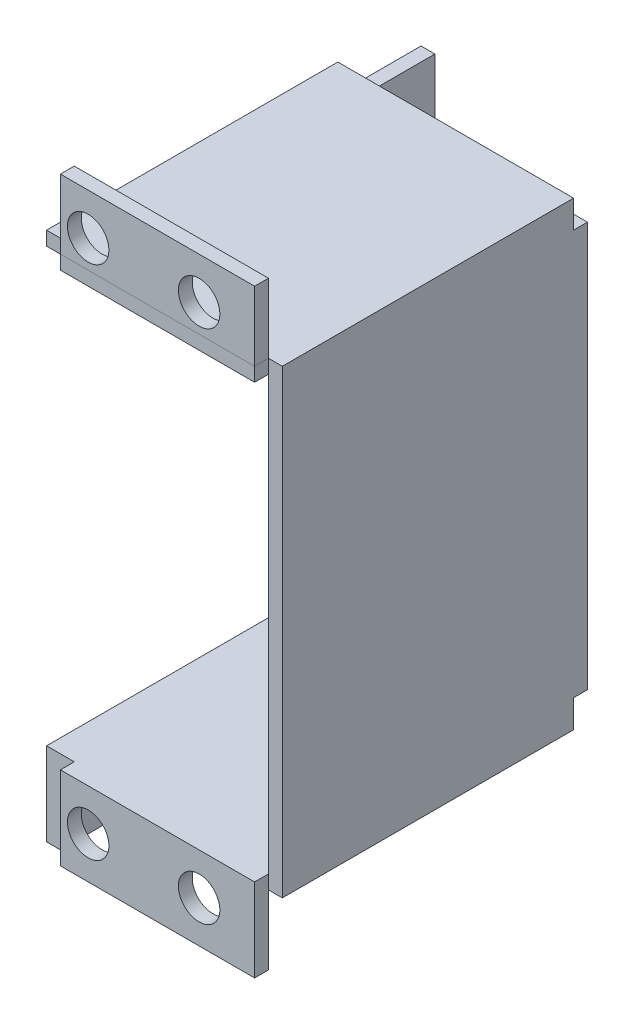
SolidWorks part; units mm, degrees
ref_plane "Front Plane" through (0, 0, 0) normal (0, 0, 1) x (1, 0, 0)
ref_plane "Top Plane" through (0, 0, 0) normal (0, 1, 0) x (1, 0, 0)
ref_plane "Right Plane" through (0, 0, 0) normal (1, 0, 0) x (0, 0, -1)
sketch "Sketch1" plane through (0, 0, 0) normal (0, 0, 1) x (1, 0, 0)
  line L1 (0, 0) -> (20.32, 0)
  line L2 (20.32, 0) -> (20.32, -39.624)
  line L3 (20.32, -39.624) -> (0, -39.624)
  line L4 (0, -39.624) -> (0, -47.244)
  dimension "D1" = 20.32
  dimension "D3" = 7.62
  dimension "D4" = 39.624
extrude "Extrude-Thin1" add sketch "Sketch1" along normal blind 26.67 thin thin type one direction reverse wall 1.27
hole_wizard "#6 Clearance Hole4" positions "Sketch13" profile "Sketch12" hole size "#6" standard "ANSI Inch"
sketch "Sketch13" plane through (1.27, 0, 0) normal (1, 0, 0) x (0, 0, -1)
  line L0 (-26.67, -40.894) -> (-26.67, -47.244) construction
  line L1 (0, -40.894) -> (0, -47.244) construction
  point P0 (-21.59, -44.069)
  point P2 (-5.08, -44.069)
  dimension "D1" = 5.08
  dimension "D2" = 5.08
sketch "Sketch12" plane through (1.27, -44.069, 21.59) normal (0, 1, 0) x (0, 0, -1)
  line L0 (0, 0) -> (0, 8.7608)
  line L1 (0, 8.7608) -> (1.8986, 7.62)
  line L2 (1.8986, 7.62) -> (1.8986, 0)
  line L5 (1.8986, 0) -> (0, 0)
  line L10 (0, 8.7608) -> (-1.8987, 7.62) construction
  line L11 (0, -6.35) -> (0, 107.95) construction
  dimension "Hole Dia." = 3.7973
  dimension "Hole Depth" = 7.62
  dimension "Drill Angle" = 118
sketch "Sketch4" plane through (0, 1.27, 0) normal (0, 1, 0) x (1, 0, 0)
  line L0 (0, -26.67) -> (21.59, -26.67) construction
  line L1 (2.54, -26.67) -> (20.32, -26.67)
  line L8 (2.54, -26.67) -> (2.54, -27.94)
  line L9 (20.32, -26.67) -> (20.32, -27.94)
  line L10 (20.32, -27.94) -> (2.54, -27.94)
  dimension "D4" = 1.27
extrude "Boss-Extrude1" add sketch "Sketch4" along normal blind 6.35
sketch "Sketch7" plane through (0, 0, 26.67) normal (0, 0, 1) x (1, 0, 0)
  line L0 (20.32, 1.27) -> (2.54, 1.27)
  line L1 (2.54, 1.27) -> (2.54, 0)
  line L2 (0, 0) -> (20.32, 0) construction
  line L3 (2.54, 0) -> (20.32, 0)
  line L4 (20.32, 0) -> (20.32, 1.27)
extrude "Boss-Extrude2" add sketch "Sketch7" along normal blind 1.27
hole_wizard "#6 Clearance Hole2" positions "Sketch6" profile "Sketch5" hole size "#6" standard "ANSI Inch" end condition through all
sketch "Sketch6" plane through (0, 0, 26.67) normal (0, 0, 1) x (1, 0, 0)
  line L1 (0, 0) -> (2.54, 0) construction
  line L3 (20.32, 7.62) -> (20.32, 1.27) construction
  point P0 (5.08, 3.81)
  point P2 (15.24, 3.81)
  dimension "D1" = 3.81
  dimension "D2" = 3.81
  dimension "D3" = 10.16
  dimension "D4" = 5.08
sketch "Sketch5" plane through (5.08, 3.81, 26.67) normal (1, 0, 0) x (0, 1, 0)
  line L0 (0, 0) -> (0, 1.27)
  line L1 (0, 1.27) -> (1.8986, 1.27)
  line L2 (1.8986, 1.27) -> (1.8986, 0)
  line L5 (1.8986, 0) -> (0, 0)
  line L11 (0, -6.35) -> (0, 107.95) construction
  dimension "Thru Hole Dia." = 3.7973
  dimension "Thru Hole Depth" = 1.27
sketch "Sketch8" plane through (0, 0, 26.67) normal (0, 0, 1) x (1, 0, 0)
  line L0 (20.32, -39.624) -> (2.54, -39.624)
  line L1 (20.32, -39.624) -> (0, -39.624) construction
  line L2 (2.54, -39.624) -> (2.54, -40.894)
  line L3 (21.59, -40.894) -> (1.27, -40.894) construction
  line L4 (2.54, -40.894) -> (20.32, -40.894)
  line L5 (20.32, -40.894) -> (20.32, -39.624)
  dimension "D1" = 17.78
extrude "Boss-Extrude3" add sketch "Sketch8" along normal blind 1.27
sketch "Sketch9" plane through (0, -40.894, 0) normal (0, -1, 0) x (1, 0, 0)
  line L1 (20.32, 27.94) -> (2.54, 27.94)
  line L2 (20.32, 27.94) -> (20.32, 26.67)
  line L3 (20.32, 26.67) -> (2.54, 26.67)
  line L4 (2.54, 27.94) -> (2.54, 26.67)
extrude "Boss-Extrude4" add sketch "Sketch9" along normal blind 6.35
hole_wizard "#6 Clearance Hole3" positions "Sketch11" profile "Sketch10" hole size "#6" standard "ANSI Inch"
sketch "Sketch11" plane through (0, 0, 27.94) normal (0, 0, 1) x (1, 0, 0)
  line L0 (20.32, -47.244) -> (20.32, -39.624) construction
  line L2 (20.32, -39.624) -> (2.54, -39.624) construction
  point P0 (15.24, -43.434)
  point P2 (5.08, -43.434)
  point P15 (15.24, -43.434)
  dimension "D1" = 5.08
  dimension "D2" = 10.16
  dimension "D3" = 3.81
sketch "Sketch10" plane through (15.24, -43.434, 27.94) normal (1, 0, 0) x (0, -1, 0)
  line L0 (0, 0) -> (0, 4.9508)
  line L1 (0, 4.9508) -> (1.8986, 3.81)
  line L2 (1.8986, 3.81) -> (1.8986, 0)
  line L5 (1.8986, 0) -> (0, 0)
  line L10 (0, 4.9508) -> (-1.8987, 3.81) construction
  line L11 (0, -6.35) -> (0, 107.95) construction
  dimension "Hole Dia." = 3.7973
  dimension "Hole Depth" = 3.81
  dimension "Drill Angle" = 118
sketch "Sketch15" plane through (0, 0, 0) normal (0, 0, -1) x (-1, 0, 0)
  line L1 (-20.32, -1.27) -> (-21.59, -1.27)
  line L2 (-20.32, -1.27) -> (-20.32, -38.354)
  line L3 (-20.32, -38.354) -> (-21.59, -38.354)
  line L4 (-21.59, -1.27) -> (-21.59, -38.354)
  line L6 (0, 1.27) -> (-21.59, 1.27) construction
  line L7 (-21.59, -40.894) -> (-1.27, -40.894) construction
  dimension "D1" = 2.54
  dimension "D2" = 2.54
extrude "Boss-Extrude5" add sketch "Sketch15" along normal blind 1.27
sketch "Sketch17" plane through (20.32, 0, 0) normal (-1, 0, 0) x (0, 0, 1)
  line L0 (-1.27, -38.354) -> (-1.27, -1.27) construction
  line L1 (-1.27, -1.27) -> (0, -1.27)
  line L2 (-1.27, -1.27) -> (-1.27, -38.354)
  line L3 (-1.27, -38.354) -> (0, -38.354)
  line L4 (0, -1.27) -> (0, -38.354)
  line L5 (-1.27, -1.27) -> (0, -1.27) construction
  line L6 (-1.27, -38.354) -> (0, -38.354) construction
  dimension "D1" = 0
  dimension "D2" = 0
extrude "Boss-Extrude14" add sketch "Sketch17" along normal blind 20.32 contours L4 L3 L2 L1
sketch "Sketch18" plane through (0, 0, -1.27) normal (0, 0, -1) x (-1, 0, 0)
  line L0 (-21.59, -38.354) -> (0, -38.354) construction
  line L1 (0, -1.27) -> (-1.27, -1.27)
  line L2 (0, -1.27) -> (0, -38.354)
  line L3 (0, -38.354) -> (-1.27, -38.354)
  line L4 (-1.27, -1.27) -> (-1.27, -38.354)
  dimension "D1" = 1.27
extrude "Boss-Extrude15" add sketch "Sketch18" along normal blind 6.35
hole_wizard "#6 Clearance Hole5" positions "Sketch20" profile "Sketch19" hole size "#6" standard "ANSI Inch"
sketch "Sketch20" plane through (1.27, 0, 0) normal (1, 0, 0) x (0, 0, -1)
  line L0 (7.62, -1.27) -> (1.27, -1.27) construction
  line L1 (7.62, -38.354) -> (1.27, -38.354) construction
  point P0 (4.445, -8.89)
  point P2 (4.445, -30.734)
  dimension "D1" = 7.62
  dimension "D2" = 7.62
sketch "Sketch19" plane through (1.27, -8.89, -4.445) normal (0, 1, 0) x (0, 0, -1)
  line L0 (0, 0) -> (0, 8.7608)
  line L1 (0, 8.7608) -> (1.8986, 7.62)
  line L2 (1.8986, 7.62) -> (1.8986, 0)
  line L5 (1.8986, 0) -> (0, 0)
  line L10 (0, 8.7608) -> (-1.8986, 7.62) construction
  line L11 (0, -6.35) -> (0, 107.95) construction
  dimension "Hole Dia." = 3.7973
  dimension "Hole Depth" = 7.62
  dimension "Drill Angle" = 118
